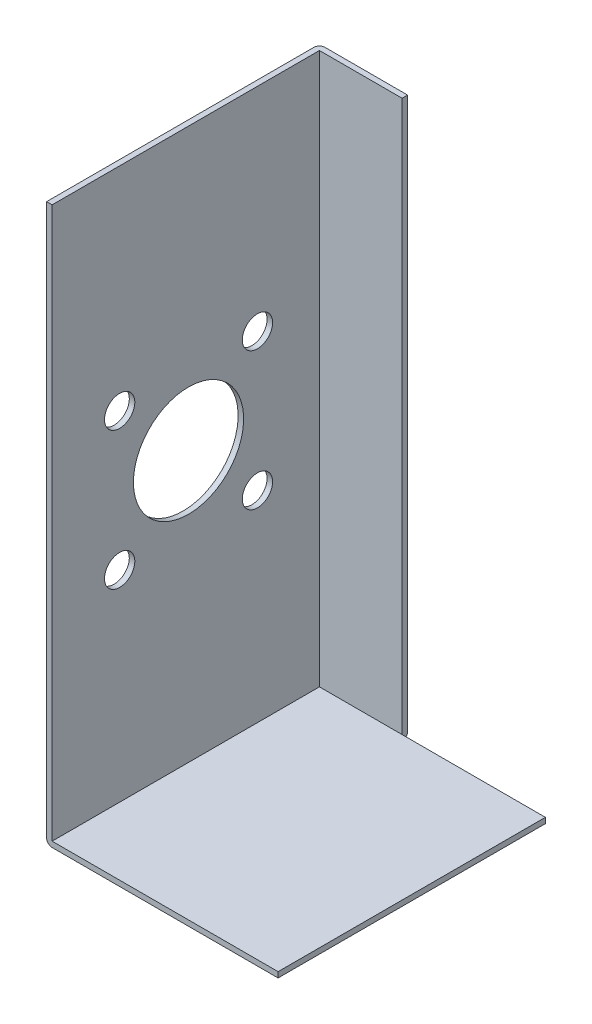
SolidWorks part; units mm, degrees
ref_plane "Front Plane" through (0, 0, 0) normal (0, 0, 1) x (1, 0, 0)
ref_plane "Top Plane" through (0, 0, 0) normal (0, 1, 0) x (1, 0, 0)
ref_plane "Right Plane" through (0, 0, 0) normal (1, 0, 0) x (0, 0, -1)
sketch "Sketch1" plane through (0, 0, 0) normal (1, 0, 0) x (0, 0, -1)
  line L1 (0, 0) -> (99, 0)
  line L2 (0, 0) -> (0, 202)
  line L3 (0, 202) -> (99, 202)
  line L4 (99, 0) -> (99, 202)
  dimension "D1" = 99
  dimension "D2" = 202
extrude "Boss-Extrude1" add sketch "Sketch1" along normal blind 2
sketch "Sketch2" plane through (2, 0, 0) normal (1, 0, 0) x (0, 0, -1)
  line L1 (0, 0) -> (97, 0)
  line L2 (0, 0) -> (0, 2)
  line L3 (0, 2) -> (97, 2)
  line L5 (97, 2) -> (97, 0)
  dimension "D1" = 2
  dimension "D2" = 97
extrude "Boss-Extrude2" add sketch "Sketch2" along normal blind 82
sketch "Sketch3" plane through (2, 0, 0) normal (1, 0, 0) x (0, 0, -1)
  line L6 (99, 202) -> (97, 202)
  line L7 (99, 202) -> (99, 0)
  line L8 (99, 0) -> (97, 0)
  line L9 (97, 202) -> (97, 0)
extrude "Boss-Extrude3" add sketch "Sketch3" along normal blind 30
fillet "Fillet1" radius 2 3 edges at (16, 0, -99) (0, 0, -49.5) (0, 101, -99)
sketch "Sketch5" plane through (0, 0, 0) normal (-1, 0, 0) x (0, 0, 1)
  line L0 (0, 202) -> (0, 2) construction
  line L1 (0, 0) -> (-97, 0) construction
  line L2 (-49.5, 100) -> (-9.9869, 100) construction
  line L3 (-49.5, 100) -> (-49.5, 144.3403) construction
  circle A0 centre (-49.5, 100) radius 20
  circle A1 centre (-24.5, 125) radius 5.5
  circle A2 centre (-74.5, 125) radius 5.5
  circle A3 centre (-24.5, 75) radius 5.5
  circle A4 centre (-74.5, 75) radius 5.5
  dimension "D1" = 49.5
  dimension "D3" = 25
  dimension "D2" = 100
  dimension "D4" = 25
extrude "Cut-Extrude1" cut sketch "Sketch5" against normal blind 41
